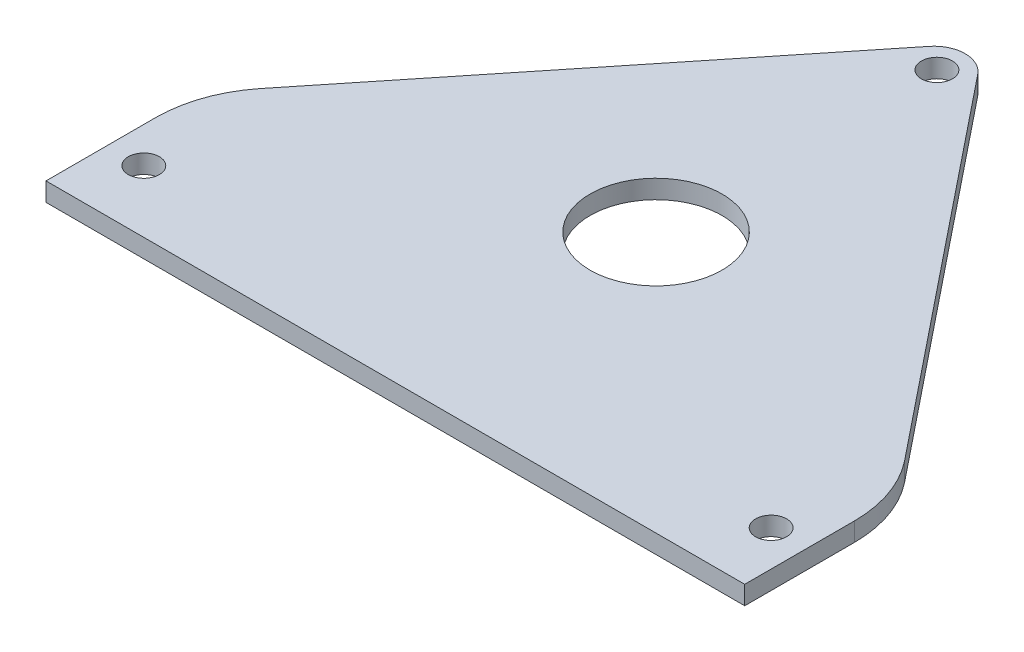
SolidWorks part; units mm, degrees
ref_plane "正面" through (0, 0, 0) normal (0, 0, 1) x (1, 0, 0)
ref_plane "平面" through (0, 0, 0) normal (0, 1, 0) x (1, 0, 0)
ref_plane "右側面" through (0, 0, 0) normal (1, 0, 0) x (0, 0, -1)
sketch "ｽｹｯﾁ1" plane through (0, 0, 0) normal (0, 1, 0) x (1, 0, 0)
  line L0 (22.5, 8) -> (22.5, 0) construction
  line L1 (0, 0) -> (45, 0)
  line L2 (0, 0) -> (0, 8)
  line L3 (0, 8) -> (45, 8)
  line L4 (45, 0) -> (45, 8)
  line L5 (0, 8) -> (2, 8) construction
  line L6 (0, 8) -> (0, 3.78) construction
  line L7 (0, 3.78) -> (2, 3.78) construction
  line L8 (2, 8) -> (2, 3.78) construction
  circle A0 centre (2, 3.78) radius 1
  circle A1 centre (43, 3.78) radius 1
  dimension "D5" = 2
  dimension "D1" = 45
  dimension "D2" = 8
  dimension "D3" = 2
  dimension "D4" = 4.22
extrude "ﾎﾞｽ - 押し出し1" add sketch "ｽｹｯﾁ1" along normal blind 1.2
sketch "ｽｹｯﾁ2" plane through (0, 1.2, 0) normal (0, 1, 0) x (1, 0, 0)
  line L0 (2, 3.78) -> (43, 3.78) construction
  line L1 (22.5, 3.78) -> (22.5, 35.15) construction
  line L2 (45, 0) -> (45, 8) construction
  line L3 (0, 8) -> (45, 8)
  line L4 (0, 8) -> (0, 38.15)
  line L5 (0, 38.15) -> (45, 38.15)
  line L6 (45, 8) -> (45, 38.15)
  circle A0 centre (22.5, 35.15) radius 1
  circle A2 centre (22.5, 17.1) radius 4.25
  dimension "D3" = 2
  dimension "D4" = 8.5
  dimension "D6" = 3
  dimension "D1" = 31.37
  dimension "D2" = 20.5
  dimension "D5" = 13.32
extrude "ﾎﾞｽ - 押し出し2" add sketch "ｽｹｯﾁ2" against normal blind 1.2
sketch "ｽｹｯﾁ6" plane through (0, 1.2, 0) normal (0, 1, 0) x (1, 0, 0)
  line L0 (0, 10.1303) -> (22.5, 38.15)
  line L1 (0, 38.15) -> (0, 0) construction
  line L2 (45, 38.15) -> (0, 38.15) construction
  line L3 (22.5, 38.15) -> (45, 10.1303)
  line L4 (45, 0) -> (45, 38.15) construction
  line L5 (45, 10.1303) -> (45, 38.15)
  line L6 (45, 38.15) -> (22.5, 38.15)
  line L7 (0, 38.15) -> (0, 10.1303)
  line L8 (22.5, 38.15) -> (0, 38.15)
extrude "ｶｯﾄ - 押し出し1" cut sketch "ｽｹｯﾁ6" against normal through all contours L8 L7 L0 | L3 L5 L6
fillet "ﾌｨﾚｯﾄ2" radius 8 2 edges at (45, 0.6, -10.1303) (0, 0.6, -10.1303)
fillet "ﾌｨﾚｯﾄ3" radius 2 1 edges at (22.5, 0.6, -38.15)
sketch "ｽｹｯﾁ7" plane through (0, 1.2, 0) normal (0, 1, 0) x (1, 0, 0)
  line L0 (45, 0) -> (45, 7.3158) construction
  line L1 (0, 0) -> (45, 0)
  line L2 (0, 0) -> (0, 0.26)
  line L3 (0, 0.26) -> (45, 0.26)
  line L4 (45, 0) -> (45, 0.26)
  circle A0 centre (2, 3.78) radius 1
  circle A1 centre (43, 3.78) radius 1
  dimension "D1" = 0.26
extrude "ﾎﾞｽ - 押し出し3" add sketch "ｽｹｯﾁ7" against normal blind 1.2
sketch "ｽｹｯﾁ8" plane through (0, 1.2, 0) normal (0, 1, 0) x (1, 0, 0)
  line L0 (45, 0) -> (45, 7.3158) construction
  line L1 (0, 0) -> (45, 0)
  line L2 (0, 0) -> (0, 0.26)
  line L3 (0, 0.26) -> (45, 0.26)
  line L4 (45, 0) -> (45, 0.26)
  dimension "D1" = 0.26
extrude "ｶｯﾄ - 押し出し2" cut sketch "ｽｹｯﾁ8" against normal through all
sketch "ｽｹｯﾁ9" plane through (0, 1.2, 0) normal (0, 1, 0) x (1, 0, 0)
  line L0 (22.5, 35.15) -> (22.5, -4.0549) construction
  line L1 (0, 0.26) -> (2.3, 0.26) construction
  line L2 (0, 0.26) -> (0, 4.26) construction
  line L3 (0, 4.26) -> (2.3, 4.26) construction
  line L4 (2.3, 0.26) -> (2.3, 4.26) construction
  circle A0 centre (2.3, 4.26) radius 1
  circle A1 centre (42.7, 4.26) radius 1
  dimension "D3" = 2
  dimension "D1" = 4
  dimension "D2" = 2.3
extrude "ｶｯﾄ - 押し出し3" cut sketch "ｽｹｯﾁ9" against normal through all
sketch "ｽｹｯﾁ10" plane through (0, 1.2, 0) normal (0, 1, 0) x (1, 0, 0)
  circle A0 centre (22.5, 17.1) radius 4.25
  circle A1 centre (22.5, 35.15) radius 1
extrude "ﾎﾞｽ - 押し出し4" add sketch "ｽｹｯﾁ10" against normal blind 1.2
sketch "ｽｹｯﾁ11" plane through (0, 1.2, 0) normal (0, 1, 0) x (1, 0, 0)
  line L0 (22.5, 0.26) -> (22.5, 17.05) construction
  line L1 (45, 0.26) -> (0, 0.26) construction
  line L2 (22.5, 0.26) -> (22.5, 35.14) construction
  circle A0 centre (22.5, 17.05) radius 4.25
  circle A1 centre (22.5, 35.14) radius 1
  dimension "D2" = 8.5
  dimension "D4" = 2
  dimension "D1" = 16.79
  dimension "D3" = 34.88
extrude "ｶｯﾄ - 押し出し4" cut sketch "ｽｹｯﾁ11" against normal through all
